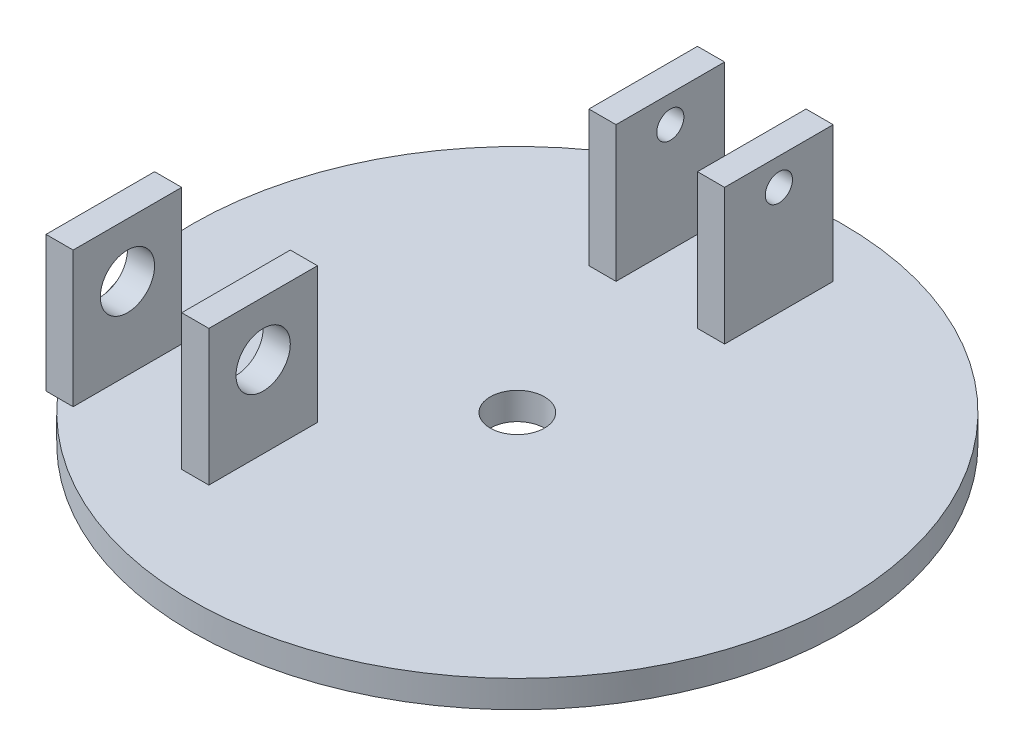
SolidWorks part; units mm, degrees
material "6061 Alloy"
ref_plane "Front Plane" through (0, 0, 0) normal (0, 0, 1) x (1, 0, 0)
ref_plane "Top Plane" through (0, 0, 0) normal (0, 1, 0) x (1, 0, 0)
ref_plane "Right Plane" through (0, 0, 0) normal (1, 0, 0) x (0, 0, -1)
sketch "Sketch1" plane through (0, 0, 0) normal (0, 1, 0) x (1, 0, 0)
  circle A0 centre (0, 0) radius 76.2
  dimension "D1" = 152.4
extrude "Boss-Extrude1" add sketch "Sketch1" along normal blind 6.35
sketch "Sketch2" plane through (0, 0, 0) normal (0, -1, 0) x (1, 0, 0)
  circle A0 centre (0, 0) radius 6.35
  dimension "D1" = 12.7
extrude "Cut-Extrude1" cut sketch "Sketch2" against normal through all
sketch "Sketch3" plane through (0, 6.35, 0) normal (0, 1, 0) x (1, 0, 0)
  line L0 (-53.1127, -38.1) -> (-27.7127, -38.1) construction
  line L1 (-59.4627, -25.4) -> (-53.1127, -25.4)
  line L2 (-59.4627, -25.4) -> (-59.4627, -50.8)
  line L3 (-59.4627, -50.8) -> (-53.1127, -50.8)
  line L4 (-53.1127, -25.4) -> (-53.1127, -50.8)
  line L5 (-27.7127, -25.4) -> (-21.3627, -25.4)
  line L6 (-27.7127, -25.4) -> (-27.7127, -50.8)
  line L7 (-27.7127, -50.8) -> (-21.3627, -50.8)
  line L8 (-21.3627, -25.4) -> (-21.3627, -50.8)
  point P10 (-40.4127, -38.1)
  dimension "D1" = 40.4127
  dimension "D2" = 6.35
  dimension "D3" = 38.1
  dimension "D4" = 25.4
  dimension "D5" = 25.4
extrude "Boss-Extrude2" add sketch "Sketch3" along normal blind 31.75
sketch "Sketch4" plane through (-21.3627, 0, 0) normal (1, 0, 0) x (0, 0, -1)
  line L0 (-38.1, 38.1) -> (-38.1, 25.4) construction
  line L1 (-50.8, 38.1) -> (-25.4, 38.1) construction
  circle A0 centre (-38.1, 25.4) radius 6.35
  dimension "D1" = 12.7
  dimension "D2" = 12.7
extrude "Cut-Extrude2" cut sketch "Sketch4" against normal up to surface (38.1 mm away) up to face at (-59.4627, 19.05, 40.0102)
sketch "Sketch5" plane through (0, 6.35, 0) normal (0, 1, 0) x (1, 0, 0)
  line L0 (-15.0127, 50.8) -> (4.0373, 50.8) construction
  line L2 (-21.3627, 38.1) -> (-15.0127, 38.1)
  line L3 (-21.3627, 38.1) -> (-21.3627, 63.5)
  line L4 (-21.3627, 63.5) -> (-15.0127, 63.5)
  line L5 (-15.0127, 38.1) -> (-15.0127, 63.5)
  line L6 (4.0373, 63.5) -> (10.3873, 63.5)
  line L7 (4.0373, 63.5) -> (4.0373, 38.1)
  line L8 (4.0373, 38.1) -> (10.3873, 38.1)
  line L9 (10.3873, 63.5) -> (10.3873, 38.1)
  point P10 (-5.4877, 50.8)
  dimension "D1" = 25.4
  dimension "D2" = 6.35
  dimension "D3" = 19.05
  dimension "D4" = 34.925
  dimension "D5" = 88.9
extrude "Boss-Extrude3" add sketch "Sketch5" along normal blind 31.75
sketch "Sketch6" plane through (-21.3627, 0, 0) normal (-1, 0, 0) x (0, 0, 1)
  line L0 (-50.8, 38.1) -> (-50.8, 31.75) construction
  line L1 (-63.5, 38.1) -> (-38.1, 38.1) construction
  circle A0 centre (-50.8, 31.75) radius 3.175
  dimension "D1" = 6.35
  dimension "D2" = 6.35
extrude "Cut-Extrude3" cut sketch "Sketch6" against normal up to surface (31.75 mm away) up to face at (10.3873, 22.225, -50.8)
